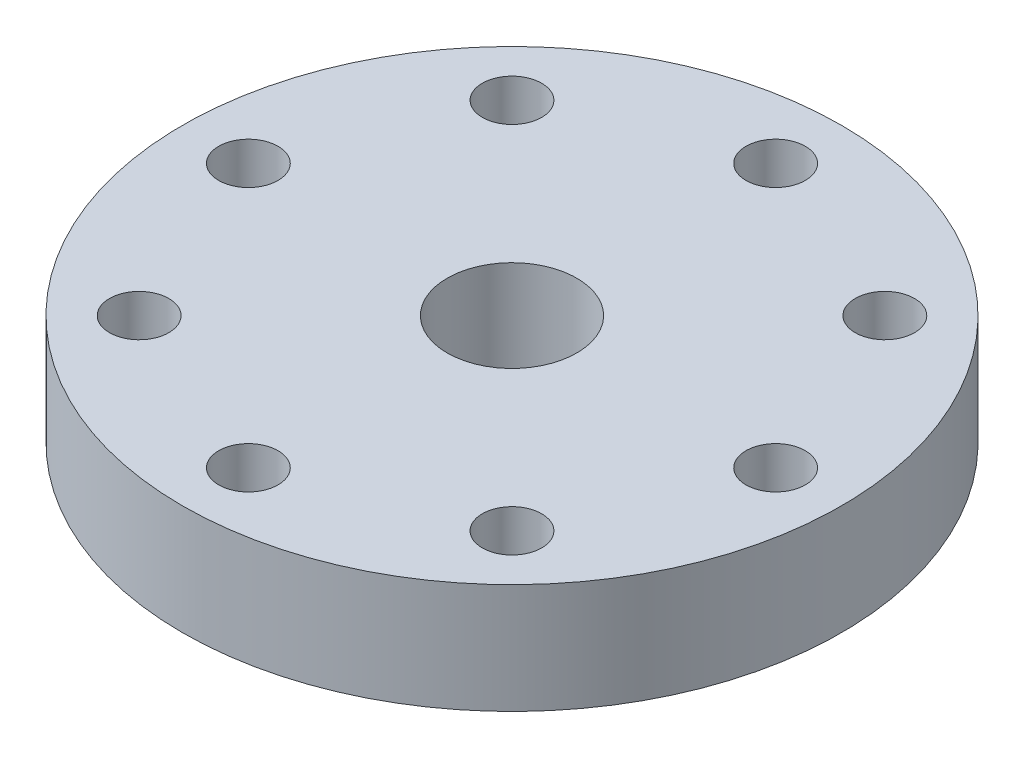
SolidWorks part; units mm, degrees
ref_plane "Plan de face" through (0, 0, 0) normal (0, 0, 1) x (1, 0, 0)
ref_plane "Plan de dessus" through (0, 0, 0) normal (0, 1, 0) x (1, 0, 0)
ref_plane "Plan de droite" through (0, 0, 0) normal (1, 0, 0) x (0, 0, -1)
sketch "Esquisse1" plane through (0, 0, 0) normal (0, 1, 0) x (1, 0, 0)
  circle A0 centre (0, 0) radius 15
  dimension "D1" = 30
extrude "Boss.-Extru.1" add sketch "Esquisse1" along normal blind 5
sketch "Esquisse2" plane through (0, 5, 0) normal (0, 1, 0) x (1, 0, 0)
  circle A0 centre (0, 0) radius 2.95
  dimension "D1" = 5.9
extrude "Enlèv. mat.-Extru.1" cut sketch "Esquisse2" against normal through all
hole_wizard "Dégagement M2.51" positions "Esquisse3" profile "Esquisse4" hole size "M2.5" standard "ISO" end condition through all
sketch "Esquisse3" plane through (0, 5, 0) normal (0, 1, 0) x (1, 0, 0)
  circle A0 centre (0, 0) radius 12 construction
  point P7 (-12, 0)
  point P12 (-8.4853, 8.4853)
  point P13 (0, 12)
  point P14 (8.4853, 8.4853)
  point P15 (12, 0)
  point P16 (8.4853, -8.4853)
  point P17 (0, -12)
  point P18 (-8.4853, -8.4853)
  point P19 (0, 0)
  dimension "D1" = 24
  dimension "D2" = 8
sketch "Esquisse4" plane through (0, 5, 0) normal (1, 0, 0) x (0, 0, 1)
  line L0 (0, 0) -> (0, 5)
  line L1 (0, 5) -> (1.35, 5)
  line L2 (1.35, 5) -> (1.35, 0)
  line L5 (1.35, 0) -> (0, 0)
  line L11 (0, -6.35) -> (0, 107.95) construction
  dimension "Diamètre du perçage jusqu'au prochain" = 2.7
  dimension "Profondeur du perçage jusqu'au prochain" = 5
